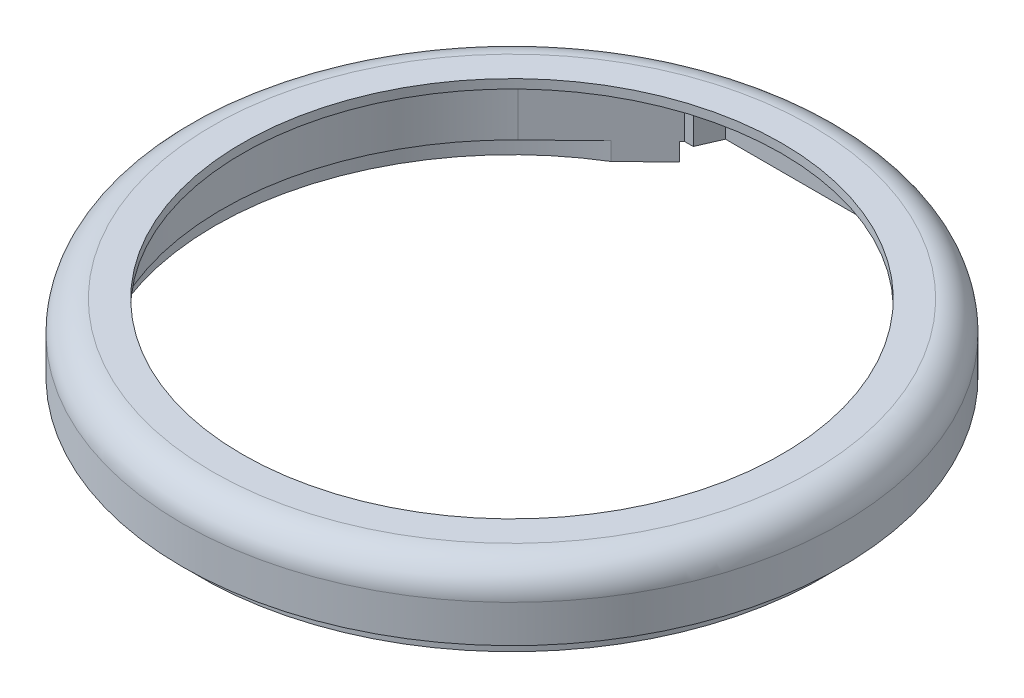
SolidWorks part; units mm, degrees
ref_plane "Front Plane" through (0, 0, 0) normal (0, 0, 1) x (1, 0, 0)
ref_plane "Top Plane" through (0, 0, 0) normal (0, 1, 0) x (1, 0, 0)
ref_plane "Right Plane" through (0, 0, 0) normal (1, 0, 0) x (0, 0, -1)
sketch "Sketch1" plane through (0, 0, 0) normal (0, 1, 0) x (1, 0, 0)
  circle A1 centre (0, 0) radius 22
  dimension "D1" = 44
extrude "Boss-Extrude1" add sketch "Sketch1" along normal blind 4.5
sketch "Sketch2" plane through (0, 0, 0) normal (0, -1, 0) x (1, 0, 0)
  circle A0 centre (0, 0) radius 20.8
  circle A1 centre (0, 0) radius 19.84
  circle A2 centre (0, 0) radius 22 construction
  dimension "D1" = 1.2
  dimension "D2" = 0.96
extrude "Boss-Extrude2" add sketch "Sketch2" along normal blind 1.2
sketch "Sketch3" plane through (0, 4.5, 0) normal (0, 1, 0) x (1, 0, 0)
  circle A0 centre (0, 0) radius 18
  dimension "D1" = 36
extrude "Cut-Extrude1" cut sketch "Sketch3" against normal through all
sketch "Sketch4" plane through (0, 0, 0) normal (0, -1, 0) x (1, 0, 0)
  line L0 (-13.4813, -13.8809) -> (-7.85, -19.35)
  line L1 (-7.85, -19.35) -> (7.85, -19.35)
  line L2 (7.85, -19.35) -> (13.4813, -13.8809)
  arc A0 (13.4813, -13.8809) -> (-13.4813, -13.8809) centre (0, 0) ccw
  arc A1 (-13.4813, -13.8809) -> (0, -19.35) centre (0, 0) ccw construction
  arc A2 (0, -19.35) -> (13.4813, -13.8809) centre (0, 0) ccw construction
  point P5 (-8.0921, -28.595)
  point P8 (0, -19.35)
  point P9 (7.85, -24.0665)
  dimension "D1" = 38.7
  dimension "D2" = 15.7
extrude "Cut-Extrude2" cut sketch "Sketch4" against normal offset from surface 0.6 and the other way through all up to face at (0, 4.5, 18)
sketch "Sketch5" plane through (0, 0, 0) normal (0, -1, 0) x (1, 0, 0)
  line L0 (-6.6, -20.85) -> (6.6, -20.85)
  line L1 (4.3821, -19.35) -> (-4.3821, -19.35) construction
  line L2 (0, -20.85) -> (0, -19.35) construction
  line L3 (-7.25, -19.35) -> (7.25, -19.35)
  line L4 (-7.63, -19.35) -> (-4.3821, -19.35) construction
  line L5 (-7.25, -19.35) -> (-6.6, -20.85)
  line L6 (7.25, -19.35) -> (6.6, -20.85)
  point P10 (0, -19.35)
  dimension "D1" = 13.2
  dimension "D2" = 1.5
  dimension "D3" = 14.5
extrude "Cut-Extrude3" cut sketch "Sketch5" against normal offset from surface 1.4 and the other way through all up to face at (0, 4.5, 18)
fillet "Fillet1" radius 2 1 edges at (0, 4.5, 22)
fillet "Fillet2" radius 1 1 edges at (0, 3.1, -20.85)
sketch "Sketch6" plane through (0, 0, 0) normal (0, -1, 0) x (1, 0, 0)
  line L5 (7.25, -19.35) -> (7.1749, -19.5233)
  line L8 (7.25, -19.35) -> (7.1749, -19.5233)
  line L9 (7.63, -19.35) -> (7.25, -19.35)
  line L10 (7.63, -19.35) -> (7.25, -19.35)
  line L11 (-7.1749, -19.5233) -> (-7.25, -19.35)
  line L12 (-7.25, -19.35) -> (-7.63, -19.35)
  line L13 (-7.1749, -19.5233) -> (-7.25, -19.35)
  line L14 (-7.25, -19.35) -> (-7.63, -19.35)
  arc A1 (7.1749, -19.5233) -> (7.63, -19.35) centre (0, 0) ccw
  arc A3 (7.1749, -19.5233) -> (7.63, -19.35) centre (0, 0) ccw
  arc A4 (-7.63, -19.35) -> (-7.1749, -19.5233) centre (0, 0) ccw
  arc A5 (-7.63, -19.35) -> (-7.1749, -19.5233) centre (0, 0) ccw
  point P4 (-3.226, -21.3683)
  dimension "D1" = 0
  dimension "D2" = 0
extrude "Cut-Extrude4" cut sketch "Sketch6" along normal through all
